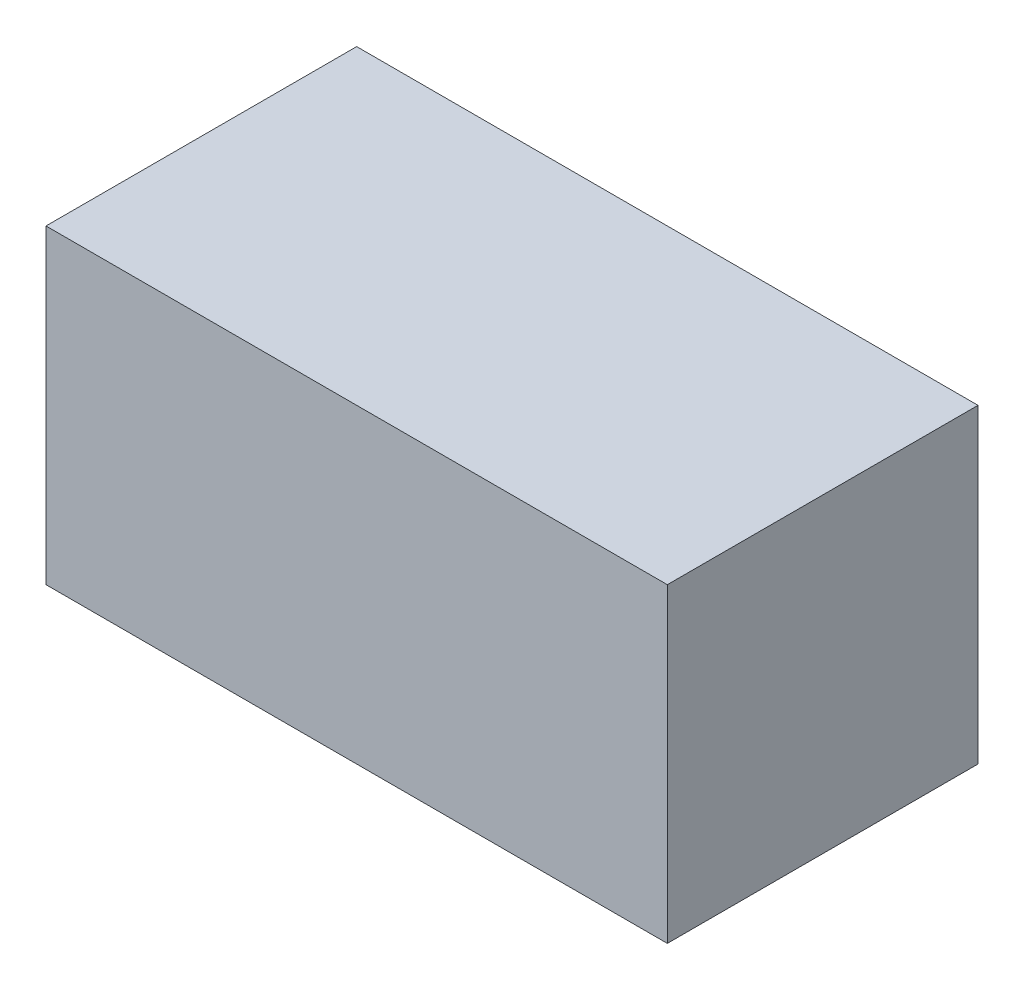
SolidWorks part; units mm, degrees
ref_plane "Front Plane" through (0, 0, 0) normal (0, 0, 1) x (1, 0, 0)
ref_plane "Top Plane" through (0, 0, 0) normal (0, 1, 0) x (1, 0, 0)
ref_plane "Right Plane" through (0, 0, 0) normal (1, 0, 0) x (0, 0, -1)
sketch "Sketch1" plane through (0, 0, 0) normal (0, 0, 1) x (1, 0, 0)
  line L1 (-20, -10) -> (20, -10)
  line L2 (-20, -10) -> (-20, 10)
  line L3 (-20, 10) -> (20, 10)
  line L4 (20, -10) -> (20, 10)
  line L5 (-20, -10) -> (20, 10) construction
  line L6 (-20, 10) -> (20, -10) construction
  point P0 (0, 0)
extrude "Boss-Extrude1" add sketch "Sketch1" along normal blind 20
